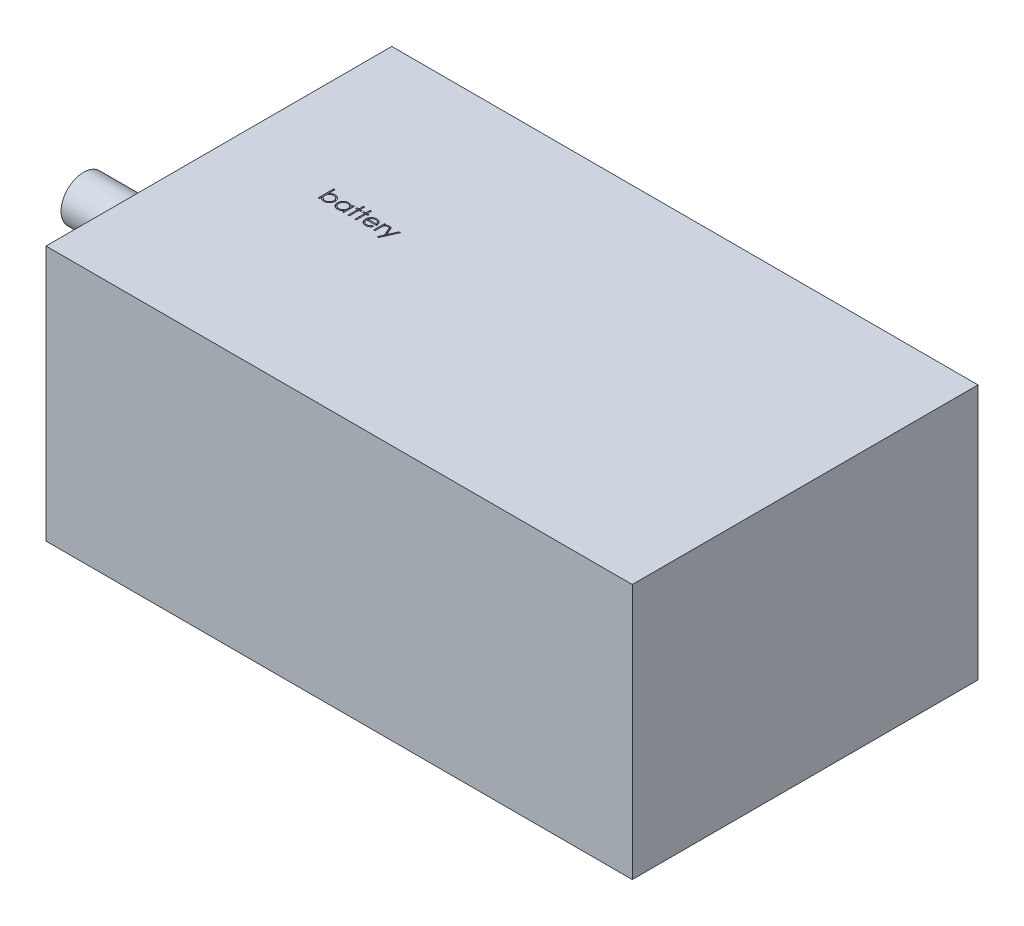
SolidWorks part; units mm, degrees
ref_plane "Front Plane" through (0, 0, 0) normal (0, 0, 1) x (1, 0, 0)
ref_plane "Top Plane" through (0, 0, 0) normal (0, 1, 0) x (1, 0, 0)
ref_plane "Right Plane" through (0, 0, 0) normal (1, 0, 0) x (0, 0, -1)
sketch "Sketch1" plane through (0, 0, 0) normal (0, 1, 0) x (1, 0, 0)
  line L1 (0, 0) -> (123.825, 0)
  line L2 (0, 0) -> (0, 73.025)
  line L3 (0, 73.025) -> (123.825, 73.025)
  line L4 (123.825, 0) -> (123.825, 73.025)
  dimension "D1" = 73.025
  dimension "D2" = 123.825
extrude "Boss-Extrude1" add sketch "Sketch1" along normal blind 53.975
sketch "Sketch2" plane through (0, 0, 0) normal (-1, 0, 0) x (0, 0, 1)
  line L0 (-73.025, 53.975) -> (-73.025, 0) construction
  line L1 (-73.025, 0) -> (0, 0) construction
  circle A0 centre (-39.6875, 26.9875) radius 4.7625
  dimension "D1" = 9.525
  dimension "D2" = 33.3375
  dimension "D3" = 26.9875
extrude "Boss-Extrude2" add sketch "Sketch2" along normal blind 31.75
sketch "Sketch4" plane through (0, 53.975, 0) normal (0, 1, 0) x (1, 0, 0)
  text T0 "battery"
extrude "Cut-Extrude1" cut sketch "Sketch4" against normal blind 0.3175
